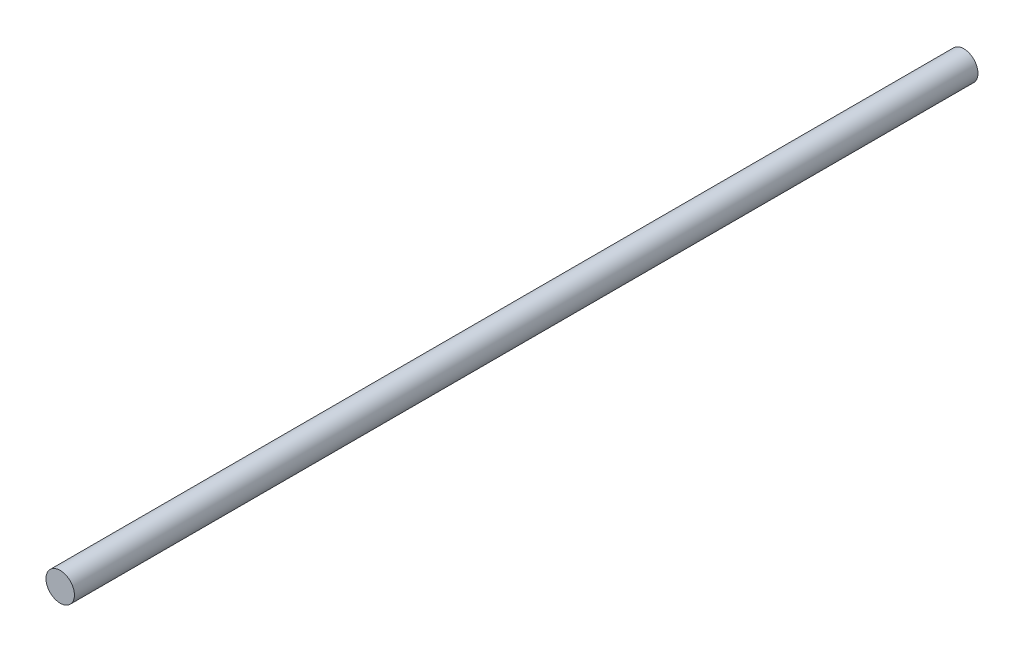
SolidWorks part; units mm, degrees
ref_plane "Front Plane" through (0, 0, 0) normal (0, 0, 1) x (1, 0, 0)
ref_plane "Top Plane" through (0, 0, 0) normal (0, 1, 0) x (1, 0, 0)
ref_plane "Right Plane" through (0, 0, 0) normal (1, 0, 0) x (0, 0, -1)
sketch "Sketch1" plane through (0, 0, 0) normal (0, 0, 1) x (1, 0, 0)
  circle A0 centre (0, 0) radius 4
  dimension "D1" = 8
extrude "Boss-Extrude1" add sketch "Sketch1" along normal blind 254
